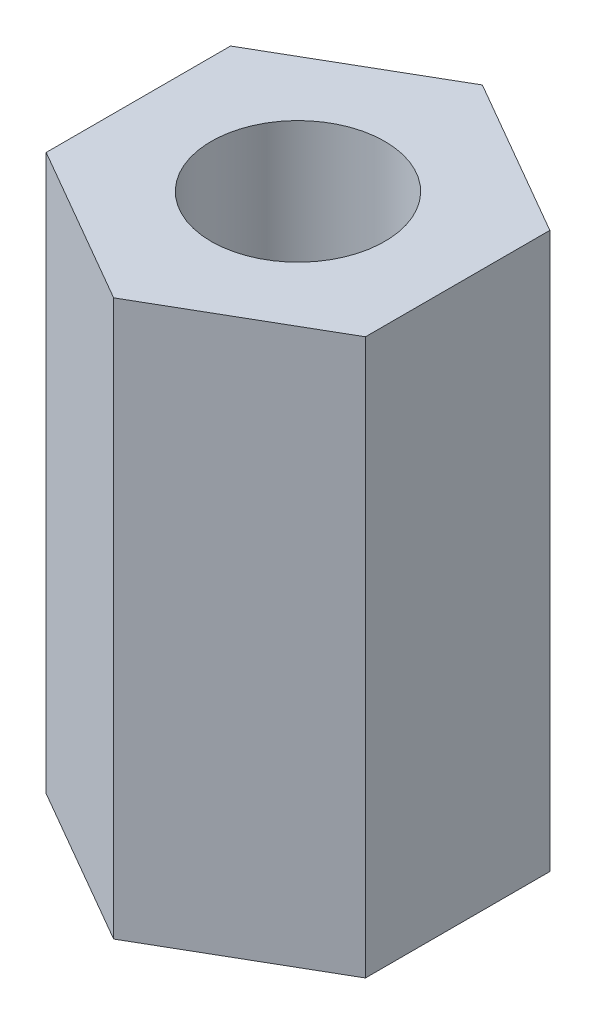
SolidWorks part; units mm, degrees
material "Brass"
ref_plane "Front Plane" through (0, 0, 0) normal (0, 0, 1) x (1, 0, 0)
ref_plane "Top Plane" through (0, 0, 0) normal (0, 1, 0) x (1, 0, 0)
ref_plane "Right Plane" through (0, 0, 0) normal (1, 0, 0) x (0, 0, -1)
sketch "Sketch1" plane through (0, 0, 0) normal (0, 1, 0) x (1, 0, 0)
  line L0 (0, -44.7868) -> (0, 44.7868) construction
  line L1 (2.3, -1.3279) -> (2.3, 1.3279)
  line L2 (2.3, 1.3279) -> (0, 2.6558)
  line L3 (0, 2.6558) -> (-2.3, 1.3279)
  line L4 (-2.3, 1.3279) -> (-2.3, -1.3279)
  line L5 (-2.3, -1.3279) -> (0, -2.6558)
  line L6 (0, -2.6558) -> (2.3, -1.3279)
  circle A0 centre (0, 0) radius 2.3 construction
  dimension "D1" = 4.6
extrude "Boss-Extrude1" add sketch "Sketch1" along normal mid plane 8
hole_wizard "M3 Tapped Hole1" positions "Sketch2" profile "Sketch3" tap size "M3" standard "ISO"
sketch "Sketch2" plane through (0, 4, 0) normal (0, 1, 0) x (1, 0, 0)
  point P0 (0, 0)
sketch "Sketch3" plane through (0, 4, 0) normal (1, 0, 0) x (0, 0, 1)
  line L0 (0, 0) -> (0, 18.2511)
  line L1 (0, 18.2511) -> (1.25, 17.5)
  line L2 (1.25, 17.5) -> (1.25, 0)
  line L5 (1.25, 0) -> (0, 0)
  line L10 (0, 18.2511) -> (-1.25, 17.5) construction
  line L11 (0, -6.35) -> (0, 107.95) construction
  dimension "Tap Drill Dia." = 2.5
  dimension "Tap Drill Depth" = 17.5
  dimension "Drill Angle" = 118
cosmetic thread "Hole Thread1" parameters "D1"=6, "D2"=3
